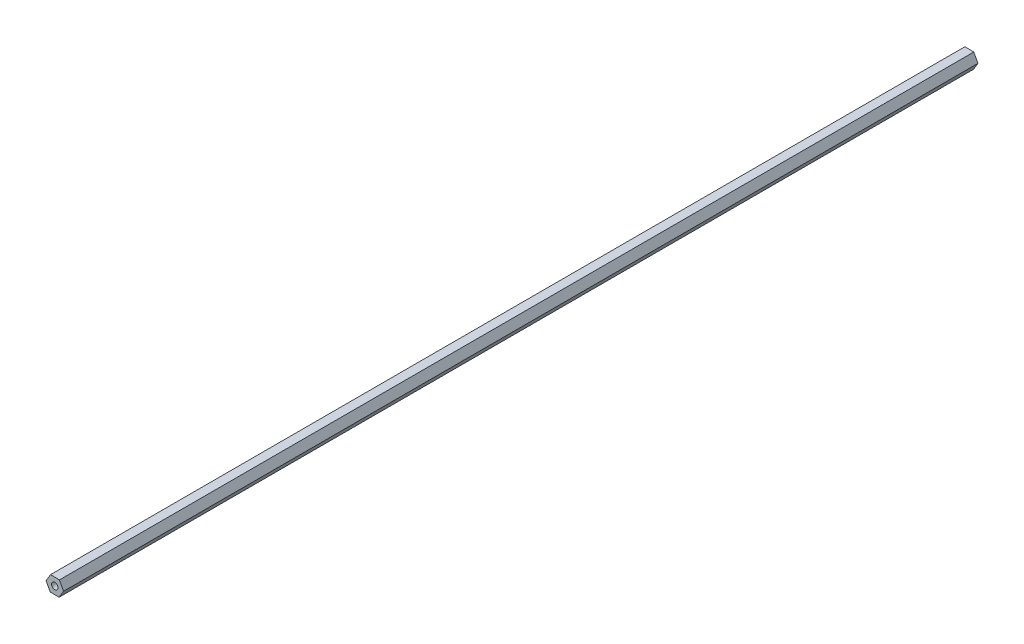
SolidWorks part; units mm, degrees
ref_plane "Front Plane" through (0, 0, 0) normal (0, 0, 1) x (1, 0, 0)
ref_plane "Top Plane" through (0, 0, 0) normal (0, 1, 0) x (1, 0, 0)
ref_plane "Right Plane" through (0, 0, 0) normal (1, 0, 0) x (0, 0, -1)
sketch "Sketch1" plane through (0, 0, 0) normal (0, 0, 1) x (1, 0, 0)
  line L1 (3.5182, -6.4332) -> (7.3304, -0.1698)
  line L2 (7.3304, -0.1698) -> (3.8122, 6.2634)
  line L3 (3.8122, 6.2634) -> (-3.5182, 6.4332)
  line L4 (-3.5182, 6.4332) -> (-7.3304, 0.1698)
  line L5 (-7.3304, 0.1698) -> (-3.8122, -6.2634)
  line L6 (-3.8122, -6.2634) -> (3.5182, -6.4332)
  circle A0 centre (0, 0) radius 6.35 construction
  circle A1 centre (0, 0) radius 2.667
  dimension "D2" = 5.334
  dimension "D1" = 12.7
extrude "Boss-Extrude2" add sketch "Sketch1" along normal blind 762 contours L1 L2 L3 L4 L5 L6 | A1
